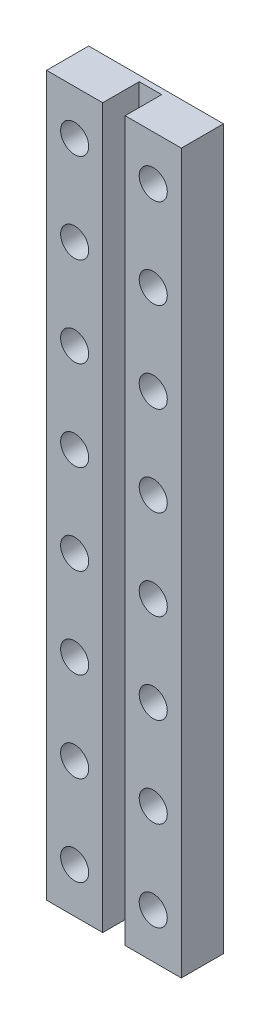
SolidWorks part; units mm, degrees
ref_plane "Plan de face" through (0, 0, 0) normal (0, 0, 1) x (1, 0, 0)
ref_plane "Plan de dessus" through (0, 0, 0) normal (0, 1, 0) x (1, 0, 0)
ref_plane "Plan de droite" through (0, 0, 0) normal (1, 0, 0) x (0, 0, -1)
sketch "Esquisse1" plane through (0, 0, 0) normal (0, 1, 0) x (1, 0, 0)
  line L0 (-2, -3.75) -> (-2, 2.75)
  line L1 (12, 3.75) -> (-12, 3.75)
  line L2 (12, 3.75) -> (12, -3.75)
  line L3 (12, -3.75) -> (2, -3.75)
  line L4 (-12, 3.75) -> (-12, -3.75)
  line L5 (12, 3.75) -> (-12, -3.75) construction
  line L6 (12, -3.75) -> (-12, 3.75) construction
  line L7 (-2, 2.75) -> (2, 2.75)
  line L8 (2, 2.75) -> (2, -3.75)
  line L9 (-2, 2.75) -> (2, -3.75) construction
  line L10 (0, 1.5046) -> (0, -2.3161) construction
  line L11 (-2, -3.75) -> (-12, -3.75)
  point P0 (0, 0)
  point P8 (0, -0.5)
  dimension "D1" = 7.5
  dimension "D2" = 24
  dimension "D3" = 1
  dimension "D4" = 10
extrude "BASE" add sketch "Esquisse1" against normal blind 128
sketch "Esquisse2" plane through (0, 0, 3.75) normal (0, 0, 1) x (1, 0, 0)
  line L0 (-7, 0) -> (-7, -38.4741) construction
  line L1 (-12, 0) -> (-2, 0) construction
  line L2 (-7, -5.5) -> (-4.873, -5.5) construction
  circle A0 centre (-7, -8) radius 2.5
  circle A1 centre (7, -8) radius 2.5
  circle A2 centre (7, -24) radius 2.5
  circle A3 centre (7, -40) radius 2.5
  circle A4 centre (7, -56) radius 2.5
  circle A5 centre (7, -72) radius 2.5
  circle A6 centre (7, -88) radius 2.5
  circle A7 centre (7, -104) radius 2.5
  circle A8 centre (7, -120) radius 2.5
  circle A11 centre (-7, -24) radius 2.5
  circle A12 centre (-7, -40) radius 2.5
  circle A13 centre (-7, -56) radius 2.5
  circle A14 centre (-7, -72) radius 2.5
  circle A15 centre (-7, -88) radius 2.5
  circle A16 centre (-7, -104) radius 2.5
  circle A17 centre (-7, -120) radius 2.5
  dimension "D2" = 5
  dimension "D1" = 5.5
  dimension "D3" = 2
  dimension "D4" = 8
extrude "TROU" cut sketch "Esquisse2" against normal through all
